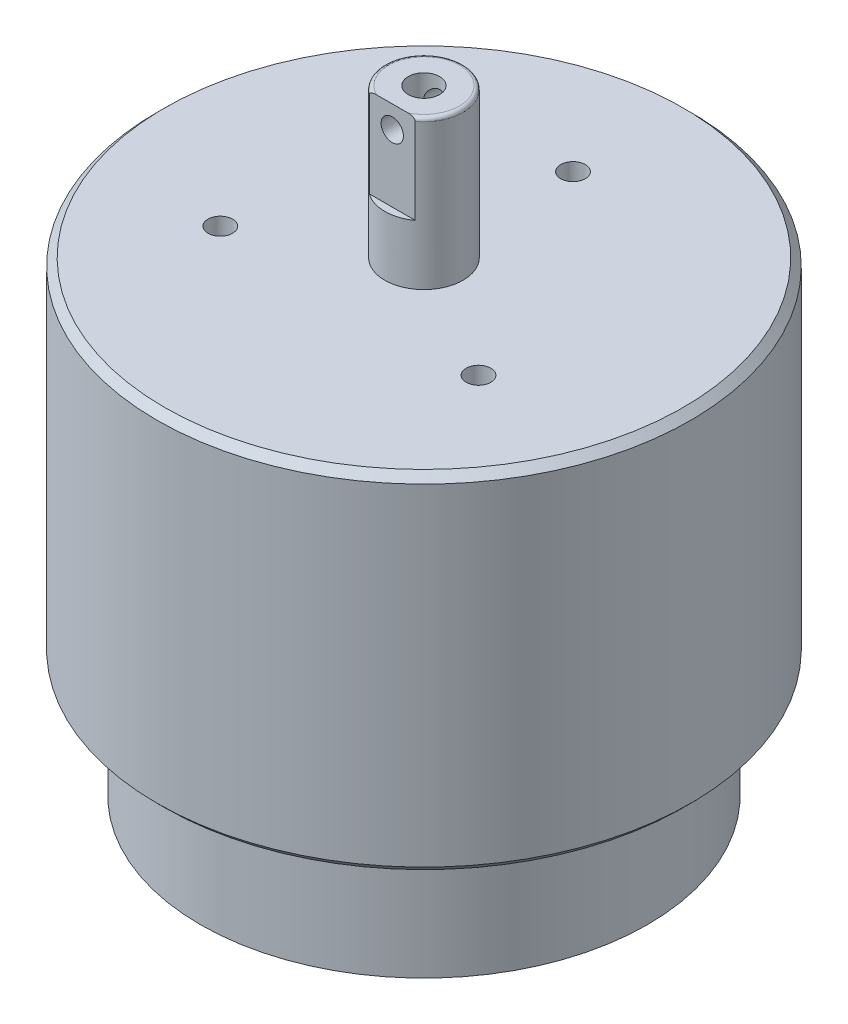
SolidWorks part; units mm, degrees
ref_plane "前视" through (0, 0, 0) normal (0, 0, 1) x (1, 0, 0)
ref_plane "上视" through (0, 0, 0) normal (0, 1, 0) x (1, 0, 0)
ref_plane "右视" through (0, 0, 0) normal (1, 0, 0) x (0, 0, -1)
sketch "草图1" plane through (0, 0, 0) normal (0, 1, 0) x (1, 0, 0)
  circle A0 centre (0, 0) radius 35.8
  dimension "D1" = 71.6
extrude "凸台-拉伸1" add sketch "草图1" along normal mid plane 46.5
sketch "草图2" plane through (0, 23.25, 0) normal (0, 1, 0) x (1, 0, 0)
  line L0 (-50.7598, 0) -> (65.2859, 0) construction
  line L1 (0, 61.6135) -> (0, -53.2896) construction
  point P5 (0, 20)
  point P6 (17.3205, -10)
  point P9 (-17.3205, -10)
  point P10 (0, 0)
  dimension "D1" = 20
  dimension "D2" = 3
hole_wizard "M4 螺纹孔1" positions "3D草图1" profile "草图3" tap size "M4" standard "Gb"
sketch3d "3D草图1"
  point P0 (0, 23.25, -20)
  point P3 (-17.3205, 23.25, 10)
  point P6 (17.3205, 23.25, 10)
sketch "草图3" plane through (0, 23.25, -20) normal (1, 0, 0) x (0, 0, 1)
  line L0 (0, 0) -> (0, 12.4914)
  line L1 (0, 12.4914) -> (1.65, 11.5)
  line L2 (1.65, 11.5) -> (1.65, 0)
  line L5 (1.65, 0) -> (0, 0)
  line L10 (0, 12.4914) -> (-1.65, 11.5) construction
  line L11 (0, -6.35) -> (0, 107.95) construction
  dimension "螺纹孔钻头直径" = 3.3
  dimension "螺纹孔钻头深度" = 11.5
  dimension "导头角度" = 118
cosmetic thread "孔螺蚊线1" parameters "D1"=8, "D2"=4
cosmetic thread "孔螺蚊线2" parameters "D1"=8, "D2"=4
cosmetic thread "孔螺蚊线3" parameters "D1"=8, "D2"=4
sketch "草图4" plane through (0, 23.25, 0) normal (0, 1, 0) x (1, 0, 0)
  circle A0 centre (0, 0) radius 5.25
  dimension "D1" = 10.5
extrude "凸台-拉伸2" add sketch "草图4" along normal blind 20
fillet "圆角1" radius 0.5 1 edges at (0, 43.25, 5.25)
sketch "草图5" plane through (0, 43.25, 0) normal (0, 1, 0) x (1, 0, 0)
  line L0 (0, 61.6135) -> (0, -53.2896) construction
  line L1 (-4.814, -4.25) -> (4.814, -4.25)
  line L2 (-4.814, -4.25) -> (-4.814, -6.25)
  line L3 (-4.814, -6.25) -> (4.814, -6.25)
  line L4 (4.814, -4.25) -> (4.814, -6.25)
  line L5 (-4.814, -4.25) -> (4.814, -6.25) construction
  line L6 (-4.814, -6.25) -> (4.814, -4.25) construction
  circle A0 centre (0, 0) radius 5.25 construction
  point P0 (0, -5.25)
  dimension "D1" = 1
extrude "切除-拉伸1" cut sketch "草图5" against normal blind 12
hole_wizard "M5 螺纹孔1" positions "3D草图2" profile "草图6" tap size "M5" standard "Gb"
sketch3d "3D草图2"
  line L0 (0, 39.9163, 0) -> (0, 48.4175, 0) construction
  point P0 (0, 43.25, 0)
sketch "草图6" plane through (0, 43.25, 0) normal (1, 0, 0) x (0, 0, 1)
  line L0 (0, 0) -> (0, 15.2618)
  line L1 (0, 15.2618) -> (2.1, 14)
  line L2 (2.1, 14) -> (2.1, 0)
  line L5 (2.1, 0) -> (0, 0)
  line L10 (0, 15.2618) -> (-2.1, 14) construction
  line L11 (0, -6.35) -> (0, 107.95) construction
  dimension "螺纹孔钻头直径" = 4.2
  dimension "螺纹孔钻头深度" = 14
  dimension "导头角度" = 118
cosmetic thread "孔螺蚊线4" parameters "D1"=10, "D2"=5
chamfer "倒角1" distance 1 angle 45 1 edges at (0, 23.25, 35.8)
sketch "草图7" plane through (0, -23.25, 0) normal (0, -1, 0) x (1, 0, 0)
  circle A0 centre (0, 0) radius 30
  dimension "D1" = 60
extrude "凸台-拉伸3" add sketch "草图7" along normal blind 17
chamfer "倒角2" distance 1 angle 45 1 edges at (0, -23.25, 35.8)
chamfer "倒角3" distance 1 distance2 3 1 edges at (0, -40.25, -30)
sketch "草图8" plane through (0, 0, 4.25) normal (0, 0, 1) x (1, 0, 0)
  line L0 (2.1213, 43.25) -> (-2.1213, 43.25) construction
  circle A0 centre (0, 40.25) radius 1.5
  dimension "D1" = 3
  dimension "D2" = 3
extrude "切除-拉伸2" cut sketch "草图8" against normal through all
